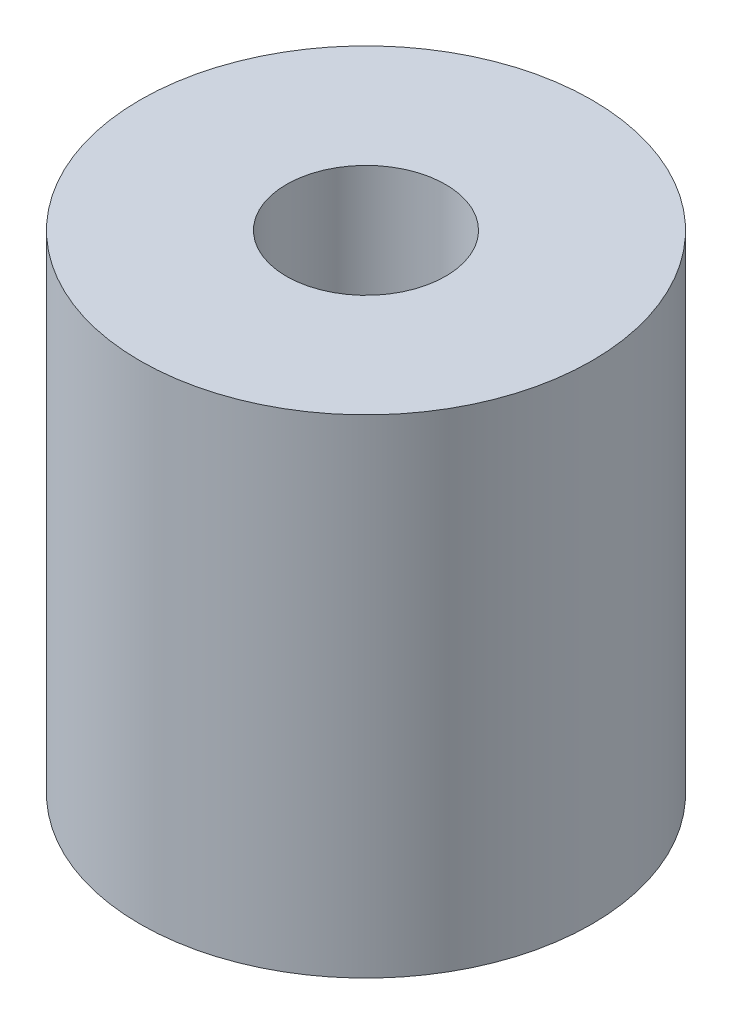
SolidWorks part; units mm, degrees
ref_plane "Front Plane" through (0, 0, 0) normal (0, 0, 1) x (1, 0, 0)
ref_plane "Top Plane" through (0, 0, 0) normal (0, 1, 0) x (1, 0, 0)
ref_plane "Right Plane" through (0, 0, 0) normal (1, 0, 0) x (0, 0, -1)
sketch "Sketch1" plane through (0, 0, 0) normal (0, 1, 0) x (1, 0, 0)
  circle A0 centre (0, 0) radius 1.632
  circle A1 centre (0, 0) radius 4.632
  dimension "D1" = 3.2639
  dimension "D2" = 3
extrude "Boss-Extrude1" add sketch "Sketch1" along normal blind 10
